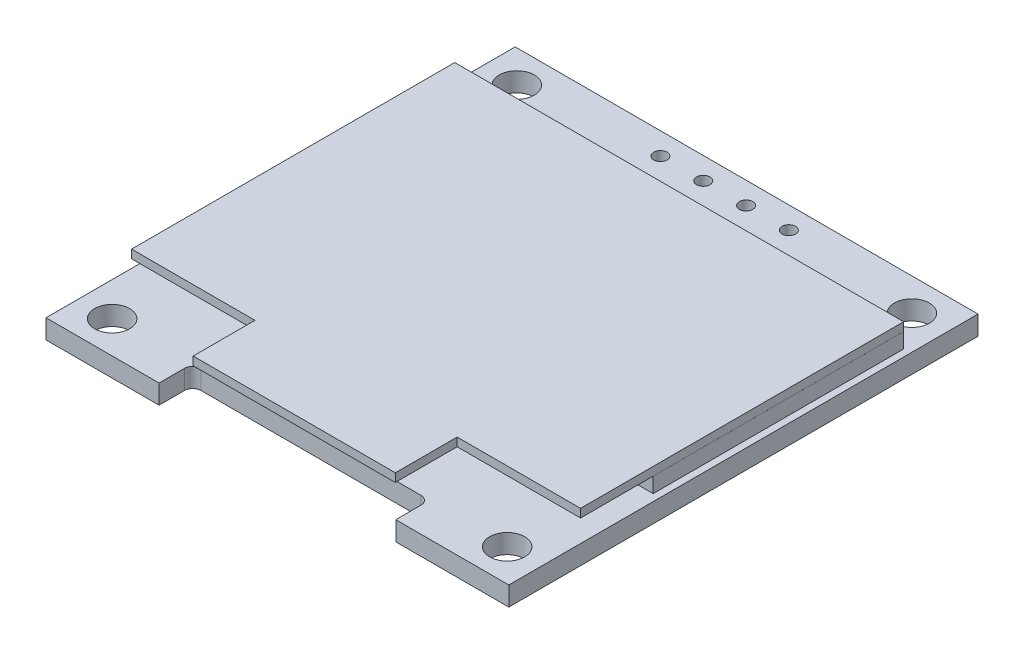
SolidWorks part; units mm, degrees
ref_plane "Front Plane" through (0, 0, 0) normal (0, 0, 1) x (1, 0, 0)
ref_plane "Top Plane" through (0, 0, 0) normal (0, 1, 0) x (1, 0, 0)
ref_plane "Right Plane" through (0, 0, 0) normal (1, 0, 0) x (0, 0, -1)
sketch "Sketch1" plane through (0, 0, 0) normal (0, 1, 0) x (1, 0, 0)
  line L0 (11.1248, -16.6277) -> (17.8348, -16.6277)
  line L1 (-9.6352, 11.2223) -> (17.8348, 11.2223)
  line L2 (-9.6352, 11.2223) -> (-9.6352, -16.6277)
  line L3 (-9.6352, -16.6277) -> (-2.9252, -16.6277)
  line L4 (17.8348, 11.2223) -> (17.8348, -16.6277)
  line L5 (4.0998, 11.2223) -> (4.0998, -14.6277) construction
  line L6 (-2.9252, -16.6277) -> (-2.9252, -15.1277)
  line L7 (-2.4252, -14.6277) -> (10.6248, -14.6277)
  line L8 (11.1248, -16.6277) -> (11.1248, -15.1277)
  circle A0 centre (-7.6252, 9.3073) radius 1.04
  circle A1 centre (15.8248, 9.3073) radius 1.04
  circle A2 centre (-7.6252, -14.7127) radius 1.04
  circle A3 centre (15.8248, -14.7127) radius 1.04
  arc A4 (10.6248, -14.6277) -> (11.1248, -15.1277) centre (10.6248, -15.1277) cw
  arc A5 (-2.9252, -15.1277) -> (-2.4252, -14.6277) centre (-2.4252, -15.1277) cw
  circle A6 centre (0.2898, 9.9184) radius 0.4
  circle A7 centre (2.8298, 9.9184) radius 0.4
  circle A8 centre (5.3698, 9.9184) radius 0.4
  circle A9 centre (7.9098, 9.9184) radius 0.4
  point P18 (11.1248, -14.6277)
  point P21 (-2.9252, -14.6277)
  dimension "D3" = 2.08
  dimension "D4" = 23.45
  dimension "D11" = 0.5
  dimension "D12" = 0.8
  dimension "D1" = 27.85
  dimension "D2" = 27.47
  dimension "D5" = 24.02
  dimension "D6" = 2.01
  dimension "D7" = 1.915
  dimension "D8" = 14.05
  dimension "D9" = 6.71
  dimension "D10" = 2
  dimension "D13" = 9.925
  dimension "D14" = 4
extrude "PCA" add sketch "Sketch1" along normal blind 1.14
sketch "Sketch2" plane through (0, 1.14, 0) normal (0, 1, 0) x (1, 0, 0)
  line L1 (-9.2252, 7.2223) -> (17.4248, 7.2223)
  line L2 (-9.2252, 7.2223) -> (-9.2252, -7.6477)
  line L3 (-9.2252, -7.6477) -> (17.4248, -7.6477)
  line L4 (17.4248, 7.2223) -> (17.4248, -7.6477)
  line L5 (-9.6352, 11.2223) -> (17.8348, 11.2223) construction
  line L6 (-9.6352, 11.2223) -> (-9.6352, -16.6277) construction
  dimension "D1" = 14.87
  dimension "D2" = 4
  dimension "D3" = 26.65
  dimension "D4" = 0.41
extrude "Bottom_glass" add sketch "Sketch2" along normal blind 0.9 separate body
sketch "Sketch5" plane through (0, 2.04, 0) normal (0, 1, 0) x (1, 0, 0)
  line L0 (9.1643, 4.3484) -> (9.1643, 3.3936)
  line L1 (9.1643, 6.3833) -> (15.5541, 6.3833)
  line L2 (9.1643, 6.3833) -> (9.1643, 5.5212)
  line L3 (9.1643, 3.3936) -> (15.5541, 3.3936)
  line L4 (15.5541, 6.3833) -> (15.5541, 3.3936)
  line L5 (9.1643, 5.5212) -> (8.463, 5.5212)
  line L6 (9.4241, 5.3212) -> (8.663, 5.3212)
  line L7 (9.1643, 4.3484) -> (8.463, 4.3484)
  line L8 (8.463, 5.5212) -> (8.463, 4.3484)
  line L9 (9.4241, 6.1496) -> (11.3133, 6.1496)
  line L10 (9.4241, 6.1496) -> (9.4241, 5.3212)
  line L11 (9.4241, 3.63) -> (11.3133, 3.63)
  line L12 (11.3133, 6.1496) -> (11.3133, 3.63)
  line L13 (8.663, 5.3212) -> (8.663, 4.5484)
  line L14 (9.4241, 4.5484) -> (8.663, 4.5484)
  line L15 (9.1643, 5.3212) -> (8.663, 5.3212) construction
  line L16 (9.1643, 4.5484) -> (8.663, 4.5484) construction
  line L17 (9.4241, 4.5484) -> (9.4241, 3.63)
  line L18 (-7.3729, 3.3936) -> (15.5541, 3.3936) construction
  text T0 "36" font "Century Gothic" height 8
  text T1 "Shots" font "Century Gothic" height 3
  point P19 (-7.3729, 3.3936)
  dimension "D1" = 0.2
extrude "text" cut sketch "Sketch5" against normal blind 0.05
sketch "Sketch3" plane through (0, 2.04, 0) normal (0, 1, 0) x (1, 0, 0)
  line L0 (-9.6352, -16.6277) -> (-2.9252, -16.6277) construction
  line L1 (-9.2252, 7.2223) -> (17.4241, 7.2223)
  line L2 (-9.2252, 7.2223) -> (-9.2252, -11.9577)
  line L3 (-9.2252, -11.9577) -> (-1.9002, -11.9577)
  line L4 (17.4241, 7.2223) -> (17.4241, -11.9577)
  line L5 (4.0998, 11.2223) -> (4.0998, -14.6277) construction
  line L6 (-1.9002, -11.9577) -> (-1.9002, -15.6277)
  line L7 (-1.9002, -15.6277) -> (10.0998, -15.6277)
  line L8 (10.0998, -11.9577) -> (10.0998, -15.6277)
  line L10 (10.0998, -11.9577) -> (17.4241, -11.9577)
  dimension "D1" = 19.18
  dimension "D2" = 12
  dimension "D3" = 1
  dimension "D4" = 6
extrude "Top_glass" add sketch "Sketch3" along normal blind 0.5
sketch "Sketch4" plane through (0, 0, 0) normal (0, -1, 0) x (1, 0, 0)
  line L1 (-8.1052, 4.5177) -> (15.6348, 4.5177)
  line L2 (-8.1052, 4.5177) -> (-8.1052, 1.2777)
  line L3 (-8.1052, 1.2777) -> (15.6348, 1.2777)
  line L4 (15.6348, 4.5177) -> (15.6348, 1.2777)
  line L5 (-1.6452, -1.9223) -> (13.0348, -1.9223)
  line L6 (-1.6452, -1.9223) -> (-1.6452, -5.9223)
  line L7 (-1.6452, -5.9223) -> (13.0348, -5.9223)
  line L8 (13.0348, -1.9223) -> (13.0348, -5.9223)
  line L10 (17.8348, -11.2223) -> (-9.6352, -11.2223) construction
  line L11 (17.8348, 16.6277) -> (17.8348, -11.2223) construction
  dimension "D1" = 14.68
  dimension "D2" = 23.74
  dimension "D3" = 4.8
  dimension "D4" = 2.2
  dimension "D5" = 3.24
  dimension "D6" = 12.5
  dimension "D7" = 4
  dimension "D8" = 5.3
extrude "SMD" add sketch "Sketch4" along normal blind 0.8 separate body
